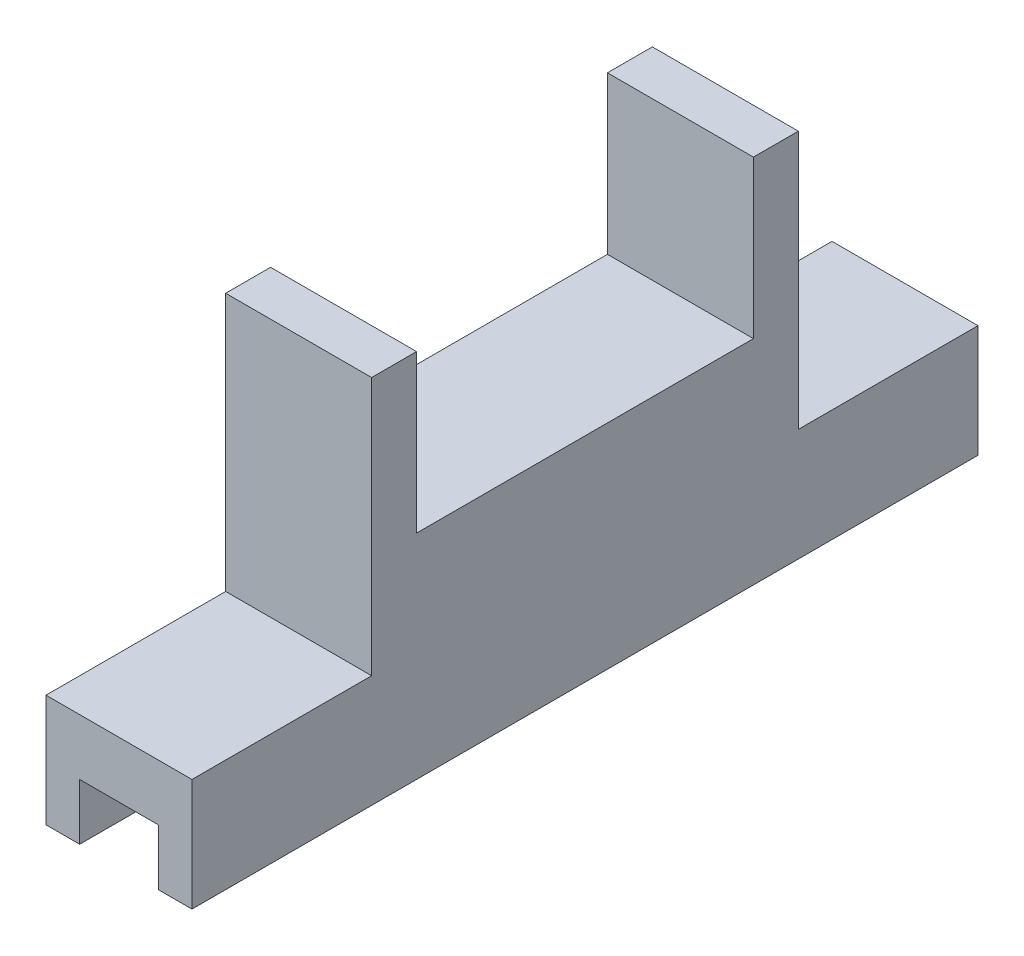
SolidWorks part; units mm, degrees
ref_plane "Front" through (0, 0, 0) normal (0, 0, 1) x (1, 0, 0)
ref_plane "Top" through (0, 0, 0) normal (0, 1, 0) x (1, 0, 0)
ref_plane "Right" through (0, 0, 0) normal (1, 0, 0) x (0, 0, -1)
sketch "Эскиз1" plane through (0, 0, 0) normal (0, 1, 0) x (1, 0, 0)
  line L1 (-22.1063, 27.7442) -> (-15.6063, 27.7442)
  line L2 (-22.1063, 27.7442) -> (-22.1063, -7.2558)
  line L3 (-22.1063, -7.2558) -> (-15.6063, -7.2558)
  line L4 (-15.6063, 27.7442) -> (-15.6063, -7.2558)
  dimension "D1" = 6.5
  dimension "D2" = 35
extrude "Бобышка-Вытянуть1" add sketch "Эскиз1" along normal blind 6
sketch "Эскиз2" plane through (0, 0, 7.2558) normal (0, 0, 1) x (1, 0, 0)
  line L0 (-22.1063, 0) -> (-15.6063, 0) construction
  line L1 (-20.1063, 2.9678) -> (-17.6063, 2.9678)
  line L2 (-20.1063, 2.9678) -> (-20.1063, 0)
  line L3 (-20.1063, 0) -> (-17.6063, 0)
  line L4 (-17.6063, 2.9678) -> (-17.6063, 0)
  line L5 (-22.1063, 6) -> (-22.1063, 0) construction
  dimension "D1" = 2.5
  dimension "D2" = 2
extrude "Вырез-Вытянуть1" cut sketch "Эскиз2" against normal blind 61
sketch "Эскиз3" plane through (0, 6, 0) normal (0, 1, 0) x (1, 0, 0)
  line L0 (-22.1063, 27.7442) -> (-22.1063, -7.2558) construction
  line L1 (-22.1063, 17.7442) -> (-15.6063, 17.7442)
  line L2 (-22.1063, 17.7442) -> (-22.1063, 2.7442)
  line L3 (-22.1063, 2.7442) -> (-15.6063, 2.7442)
  line L4 (-15.6063, 17.7442) -> (-15.6063, 2.7442)
  line L5 (-15.6063, -7.2558) -> (-15.6063, 27.7442) construction
  line L6 (-15.6063, 27.7442) -> (-22.1063, 27.7442) construction
  dimension "D1" = 15
  dimension "D2" = 10
extrude "Бобышка-Вытянуть2" add sketch "Эскиз3" along normal blind 4.5
sketch "Эскиз4" plane through (0, 0, 7.2558) normal (0, 0, 1) x (1, 0, 0)
  line L0 (-15.6063, 6) -> (-15.6063, 0) construction
  line L1 (-22.1063, 0) -> (-15.6063, 0)
  line L2 (-22.1063, 0) -> (-22.1063, 1)
  line L3 (-22.1063, 1) -> (-15.6063, 1)
  line L4 (-15.6063, 0) -> (-15.6063, 1)
  dimension "D1" = 1
extrude "Вырез-Вытянуть2" cut sketch "Эскиз4" against normal blind 503.5
sketch "Эскиз5" plane through (0, 6, 0) normal (0, 1, 0) x (1, 0, 0)
  line L0 (-15.6063, 17.7442) -> (-15.6063, 27.7442) construction
  line L1 (-15.6063, 19.7442) -> (-22.1063, 19.7442)
  line L2 (-15.6063, 19.7442) -> (-15.6063, 17.7442)
  line L3 (-15.6063, 17.7442) -> (-22.1063, 17.7442)
  line L4 (-22.1063, 19.7442) -> (-22.1063, 17.7442)
  dimension "D1" = 2
extrude "Бобышка-Вытянуть3" add sketch "Эскиз5" along normal blind 11.5
sketch "Эскиз6" plane through (0, 6, 0) normal (0, 1, 0) x (1, 0, 0)
  line L0 (-22.1063, 2.7442) -> (-22.1063, -7.2558) construction
  line L1 (-15.6063, 2.7442) -> (-22.1063, 2.7442)
  line L2 (-15.6063, 2.7442) -> (-15.6063, 0.7442)
  line L3 (-15.6063, 0.7442) -> (-22.1063, 0.7442)
  line L4 (-22.1063, 2.7442) -> (-22.1063, 0.7442)
  dimension "D1" = 2
extrude "Бобышка-Вытянуть4" add sketch "Эскиз6" along normal blind 11.5
sketch "Эскиз7" plane through (0, 0, 7.2558) normal (0, 0, 1) x (1, 0, 0)
  line L0 (-15.6063, 1) -> (-17.6063, 1) construction
  line L1 (-20.6063, 3.5) -> (-17.1063, 3.5)
  line L2 (-20.6063, 3.5) -> (-20.6063, 1)
  line L3 (-20.6063, 1) -> (-17.1063, 1)
  line L4 (-17.1063, 3.5) -> (-17.1063, 1)
  line L5 (-22.1063, 6) -> (-22.1063, 1) construction
  dimension "D1" = 3.5
  dimension "D2" = 1.5
  dimension "D3" = 2.5
extrude "Вырез-Вытянуть3" cut sketch "Эскиз7" against normal blind 90.5
